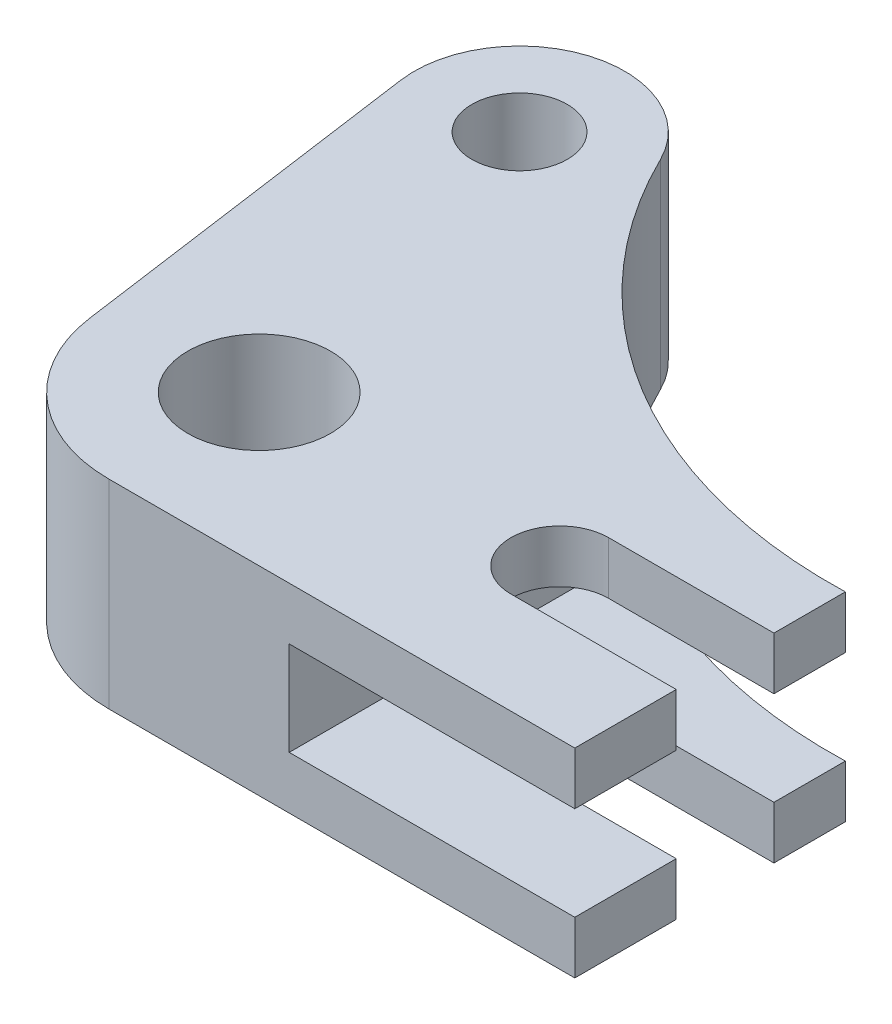
SolidWorks part; units mm, degrees
material "AISI 1020 Steel, Cold Rolled"
ref_plane "Front Plane" through (0, 0, 0) normal (0, 0, 1) x (1, 0, 0)
ref_plane "Top Plane" through (0, 0, 0) normal (0, 1, 0) x (1, 0, 0)
ref_plane "Right Plane" through (0, 0, 0) normal (1, 0, 0) x (0, 0, -1)
sketch "Sketch1" plane through (0, 0, 0) normal (0, 1, 0) x (1, 0, 0)
  line L0 (0, 0) -> (-62, 0)
  line L1 (-62, 0) -> (-62, 20) construction
  line L2 (-62, 20) -> (-62, 43.1453) construction
  line L3 (-62, 20) -> (-74.6821, 67.3304) construction
  line L4 (-88.547, 65.39) -> (-81.807, 17.2281)
  line L5 (0, 36) -> (0, 103) construction
  line L6 (-22, 26.5) -> (0, 26.5)
  line L7 (-22, 13.5) -> (0, 13.5)
  line L8 (0, 0) -> (0, 13.5)
  line L9 (0, 26.5) -> (0, 36)
  circle A0 centre (-62, 20) radius 9.5
  circle A1 centre (-74.6821, 67.3304) radius 6.35
  arc A2 (-81.807, 17.2281) -> (-62, 0) centre (-62, 20) ccw
  arc A3 (-62.1103, 73.4906) -> (-88.547, 65.39) centre (-74.6821, 67.3304) ccw
  arc A4 (-22, 26.5) -> (-22, 13.5) centre (-22, 20) ccw
  arc A5 (-62.1103, 73.4906) -> (0, 36) centre (-1.945, 102.9718) ccw
  point P13 (0, 20)
  dimension "D3" = 19
  dimension "D6" = 12.7
  dimension "D7" = 28
  dimension "D8" = 20
  dimension "D10" = 6.5
  dimension "D17" = 134
  dimension "D1" = 62
  dimension "D2" = 20
  dimension "D4" = 15
  dimension "D5" = 49
  dimension "D9" = 22
  dimension "D11" = 36
  dimension "D12" = 13.5
  dimension "D13" = 26.5
  dimension "D14" = 22
  dimension "D15" = 9.5
  dimension "D16" = 67
extrude "Boss-Extrude1" add sketch "Sketch1" along normal mid plane 26.5
sketch "Sketch2" plane through (0, 0, 0) normal (1, 0, 0) x (0, 0, -1)
  line L0 (0, 13.25) -> (0, -13.25) construction
  line L7 (0, -6.25) -> (0, 6.25)
  line L8 (0, 6.25) -> (73.3389, 6.25)
  line L9 (73.3389, 6.25) -> (73.3389, -6.25)
  line L10 (73.3389, -6.25) -> (0, -6.25)
  line L11 (0, -13.25) -> (13.5, -13.25) construction
  line L12 (0, 13.25) -> (13.5, 13.25) construction
  dimension "D1" = 7
  dimension "D2" = 7
  dimension "D3" = 73.3389
extrude "Cut-Extrude3" cut sketch "Sketch2" against normal blind 38 contours L8 L9 L10 L7
sketch "Sketch4" plane through (0, 13.25, 0) normal (0, 1, 0) x (1, 0, 0)
  line L0 (-57.9489, 58.3304) -> (-51.9064, 58.3304)
  line L1 (-88.547, 65.39) -> (-81.807, 17.2281) construction
  line L2 (-86.7667, 52.6688) -> (-88.547, 65.39)
  arc A0 (-62.1103, 73.4906) -> (0, 36) centre (-1.945, 102.9718) ccw construction
  arc A1 (-86.7667, 52.6688) -> (-57.9489, 58.3304) centre (-74.6821, 67.3304) ccw
  arc A2 (-51.9064, 58.3304) -> (-56.0747, 63.4879) centre (-1.945, 102.9718) cw
  arc A4 (-57.9489, 58.3304) -> (-86.7667, 52.6688) centre (-74.6821, 67.3304) cw
  arc A5 (-88.547, 65.39) -> (-62.1103, 73.4906) centre (-74.6821, 67.3304) cw
  arc A6 (-62.1103, 73.4906) -> (-56.0747, 63.4879) centre (-1.945, 102.9718) ccw
  dimension "D1" = 38
  dimension "D3" = 9
  dimension "D4" = 44.6414
  dimension "D5" = 67
  dimension "D2" = 9
equation "\"A\"= 62mm"
equation "\"B\"= 20mm"
equation "\"C\"= 26.50mm"
